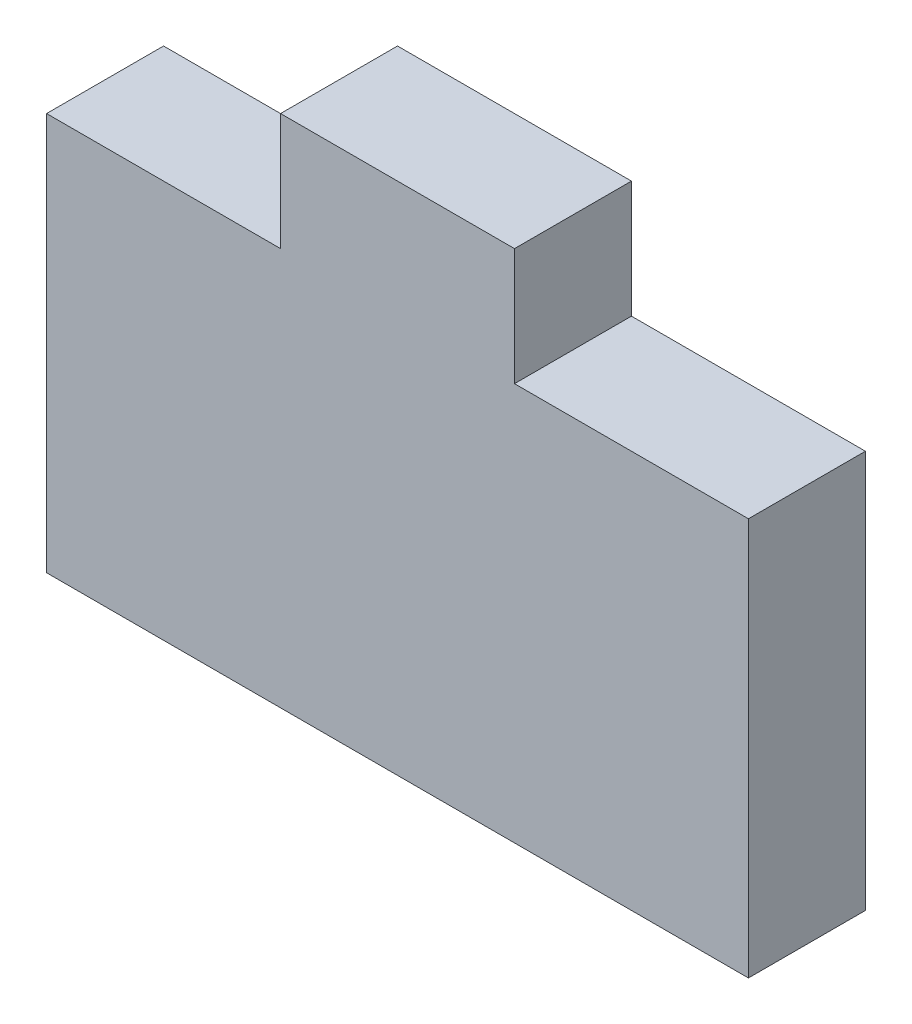
SolidWorks part; units mm, degrees
ref_plane "Front Plane" through (0, 0, 0) normal (0, 0, 1) x (1, 0, 0)
ref_plane "Top Plane" through (0, 0, 0) normal (0, 1, 0) x (1, 0, 0)
ref_plane "Right Plane" through (0, 0, 0) normal (1, 0, 0) x (0, 0, -1)
sketch "Sketch2" plane through (0, 0, 0) normal (0, 0, 1) x (1, 0, 0)
  line L1 (0, 0) -> (57.15, 0)
  line L2 (0, 0) -> (0, 41.91)
  line L3 (0, 41.91) -> (57.15, 41.91)
  line L4 (57.15, 0) -> (57.15, 41.91)
  line L5 (0, 41.91) -> (19.05, 41.91)
  line L6 (0, 41.91) -> (0, 32.385)
  line L7 (0, 32.385) -> (19.05, 32.385)
  line L8 (19.05, 41.91) -> (19.05, 32.385)
  line L9 (57.15, 41.91) -> (38.1, 41.91)
  line L10 (57.15, 41.91) -> (57.15, 32.385)
  line L11 (57.15, 32.385) -> (38.1, 32.385)
  line L12 (38.1, 41.91) -> (38.1, 32.385)
  dimension "D1" = 41.91
  dimension "D2" = 9.525
  dimension "D3" = 19.05
  dimension "D4" = 19.05
  dimension "D5" = 19.05
extrude "Boss-Extrude1" add sketch "Sketch2" along normal blind 9.525 contours L12 L3 L8 L7 L2 L1 L4 L11
